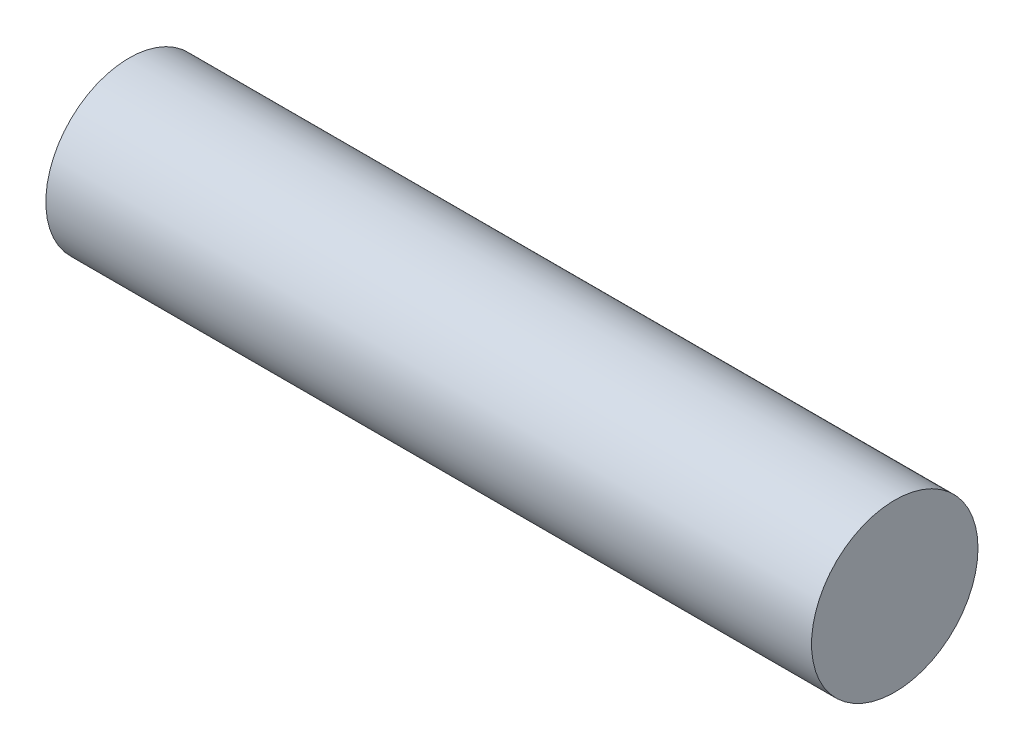
SolidWorks part; units mm, degrees
ref_plane "Front Plane" through (0, 0, 0) normal (0, 0, 1) x (1, 0, 0)
ref_plane "Top Plane" through (0, 0, 0) normal (0, 1, 0) x (1, 0, 0)
ref_plane "Right Plane" through (0, 0, 0) normal (1, 0, 0) x (0, 0, -1)
sketch "Sketch1" plane through (0, 0, 0) normal (1, 0, 0) x (0, 0, -1)
  circle A0 centre (0, 0) radius 15.875
  dimension "D1" = 31.75
extrude "Boss-Extrude1" add sketch "Sketch1" along normal blind 146.05
